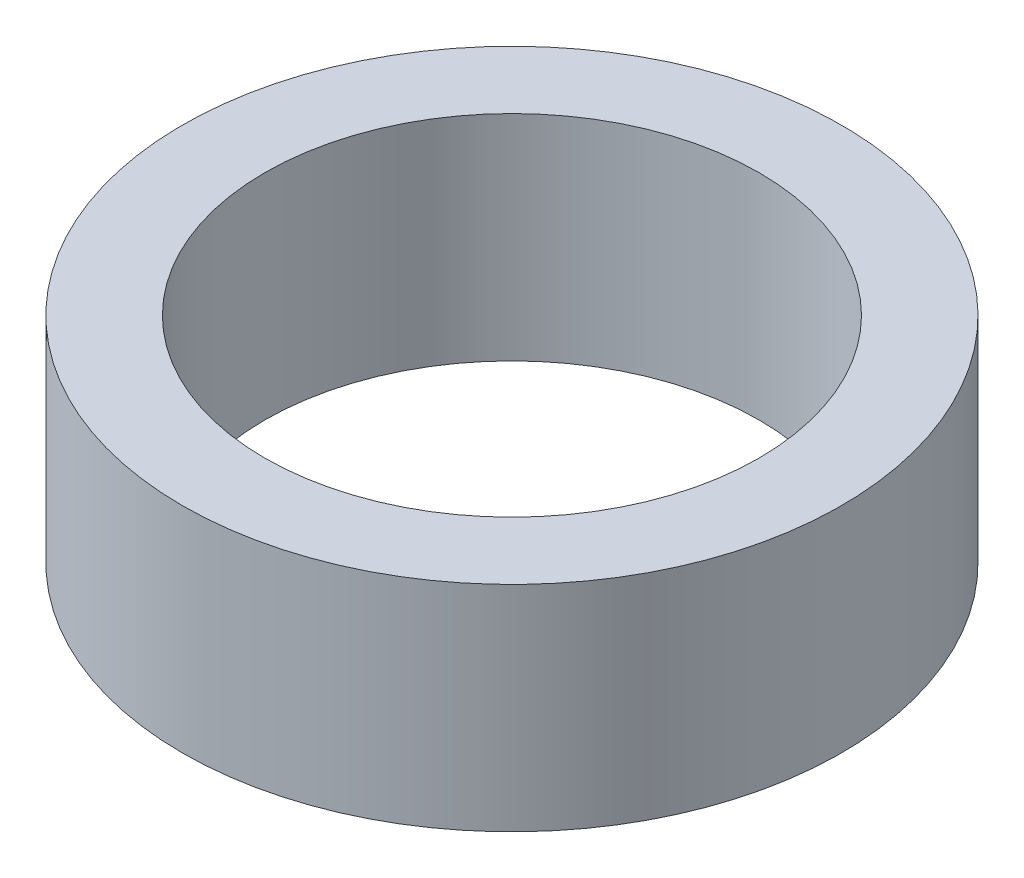
SolidWorks part; units mm, degrees
ref_plane "Front Plane" through (0, 0, 0) normal (0, 0, 1) x (1, 0, 0)
ref_plane "Top Plane" through (0, 0, 0) normal (0, 1, 0) x (1, 0, 0)
ref_plane "Right Plane" through (0, 0, 0) normal (1, 0, 0) x (0, 0, -1)
sketch "Sketch1" plane through (0, 0, 0) normal (0, 1, 0) x (1, 0, 0)
  circle A0 centre (0, 0) radius 1.5
  circle A1 centre (0, 0) radius 2
  dimension "D1" = 4
  dimension "D2" = 3
extrude "Boss-Extrude1" add sketch "Sketch1" along normal blind 1.3
